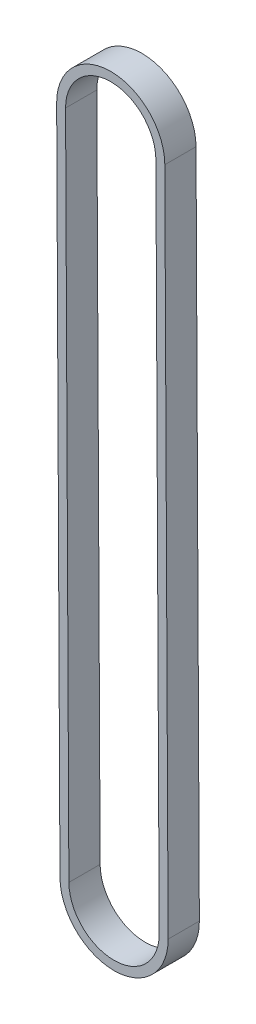
SolidWorks part; units mm, degrees
material "BUTYL"
ref_plane "前视基准面" through (0, 0, 0) normal (0, 0, 1) x (1, 0, 0)
ref_plane "上视基准面" through (0, 0, 0) normal (0, 1, 0) x (1, 0, 0)
ref_plane "右视基准面" through (0, 0, 0) normal (1, 0, 0) x (0, 0, -1)
sketch "草图2" plane through (0, 0, 0) normal (0, 0, 1) x (1, 0, 0)
  line L0 (0, 0) -> (1, 0) construction
  line L1 (0, 0) -> (0, 1) construction
  line L2 (-10.1249, -0.0503) -> (-10.8697, 149.9479)
  line L3 (9.3801, 150.0484) -> (10.1249, 0.0503)
  arc A0 (10.1249, 0.0503) -> (-10.1249, -0.0503) centre (0, 0) cw
  arc A1 (-10.8697, 149.9479) -> (9.3801, 150.0484) centre (-0.7448, 149.9982) cw
extrude "拉伸-薄壁1" add sketch "草图2" along normal mid plane 7 thin thin type one direction wall 2
